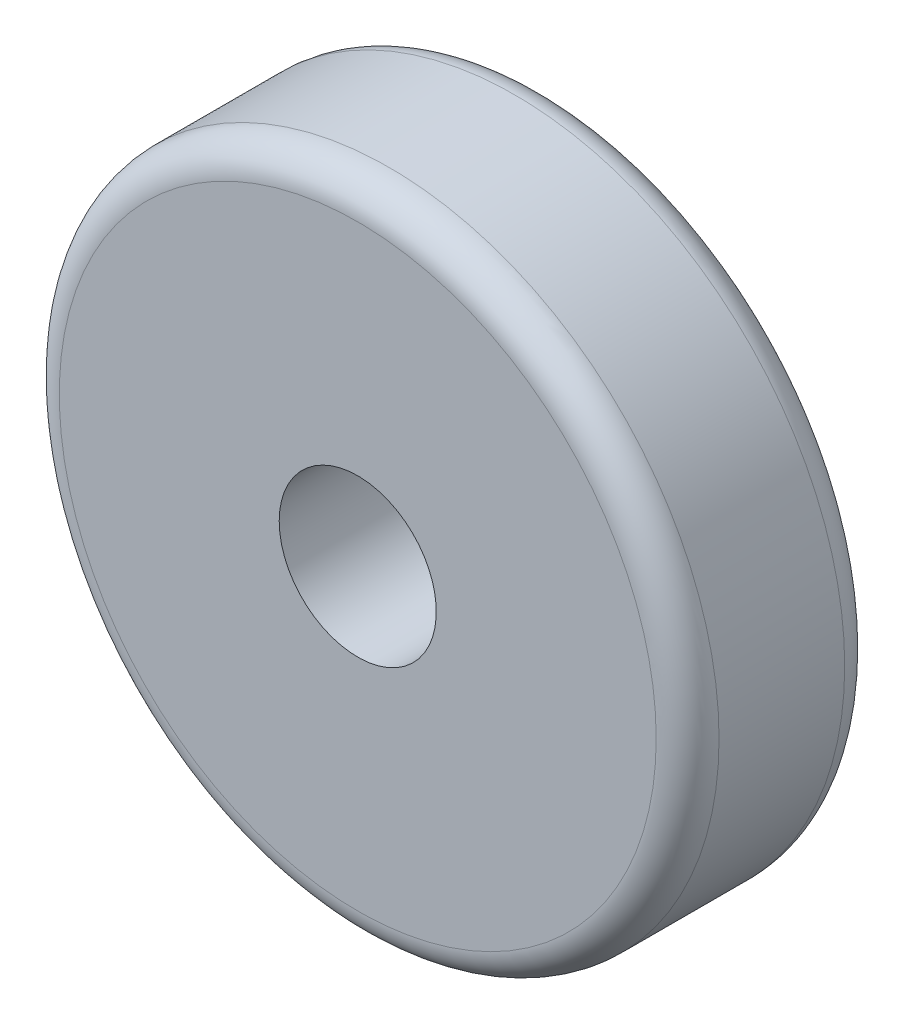
SolidWorks part; units mm, degrees
ref_plane "Front Plane" through (0, 0, 0) normal (0, 0, 1) x (1, 0, 0)
ref_plane "Top Plane" through (0, 0, 0) normal (0, 1, 0) x (1, 0, 0)
ref_plane "Right Plane" through (0, 0, 0) normal (1, 0, 0) x (0, 0, -1)
sketch "Sketch1" plane through (0, 0, 0) normal (0, 0, 1) x (1, 0, 0)
  circle A0 centre (0, 0) radius 10.5
  dimension "D1" = 21
extrude "Boss-Extrude1" add sketch "Sketch1" along normal blind 6
sketch "Sketch2" plane through (0, 0, 0) normal (0, 0, -1) x (-1, 0, 0)
  circle A0 centre (0, 0) radius 2.5
  dimension "D1" = 5
extrude "Cut-Extrude1" cut sketch "Sketch2" against normal blind 6
fillet "Fillet1" radius 1 2 edges at (10.5, 0, 6) (10.5, 0, 0)
sketch "Sketch3" plane through (0, 0, 0) normal (0, 0, -1) x (-1, 0, 0)
  line L0 (-10.1504, 0) -> (10.0348, 0) construction
  line L1 (0, 9) -> (0, -11.8711) construction
  line L2 (-0.5, 8.9861) -> (-0.5, 3.4641)
  line L3 (0.5, 8.9861) -> (0.5, 3.4641)
  line L4 (-8.9861, -0.5) -> (-3.4641, -0.5)
  line L5 (-8.9861, 0.5) -> (-3.4641, 0.5)
  line L7 (-10.1504, 0.5) -> (10.0348, 0.5) construction
  line L8 (-10.1504, -0.5) -> (10.0348, -0.5) construction
  line L9 (0, 9.3552) -> (0, -11.8711) construction
  line L10 (-0.5, -3.4641) -> (-0.5, -8.9861)
  line L11 (0.5, -3.4641) -> (0.5, -8.9861)
  line L12 (-0.5, 9.3552) -> (-0.5, -11.8711) construction
  line L13 (3.4641, -0.5) -> (8.9861, -0.5)
  line L14 (0.5, 9.3552) -> (0.5, -11.8711) construction
  line L15 (3.4641, 0.5) -> (8.9861, 0.5)
  arc A0 (-3.4641, -0.5) -> (-0.5, -3.4641) centre (0, 0) ccw
  arc A1 (-0.5, 8.9861) -> (-8.9861, 0.5) centre (0, 0) ccw
  arc A2 (0.5, -3.4641) -> (3.4641, -0.5) centre (0, 0) ccw
  arc A3 (3.4641, 0.5) -> (0.5, 3.4641) centre (0, 0) ccw
  arc A4 (-0.5, 3.4641) -> (-3.4641, 0.5) centre (0, 0) ccw
  arc A5 (8.9861, 0.5) -> (0.5, 8.9861) centre (0, 0) ccw
  arc A6 (0.5, -8.9861) -> (8.9861, -0.5) centre (0, 0) ccw
  arc A7 (-8.9861, -0.5) -> (-0.5, -8.9861) centre (0, 0) ccw
  point P31 (8.9861, -0.5)
  point P32 (8.9861, -0.4793)
  dimension "D1" = 7
  dimension "D2" = 18
  dimension "D7" = 0.5
  dimension "D8" = 0.5
  dimension "D3" = 0.5
  dimension "D4" = 0.5
  dimension "D5" = 0.5
  dimension "D6" = 0.5
extrude "Cut-Extrude2" cut sketch "Sketch3" against normal blind 2
